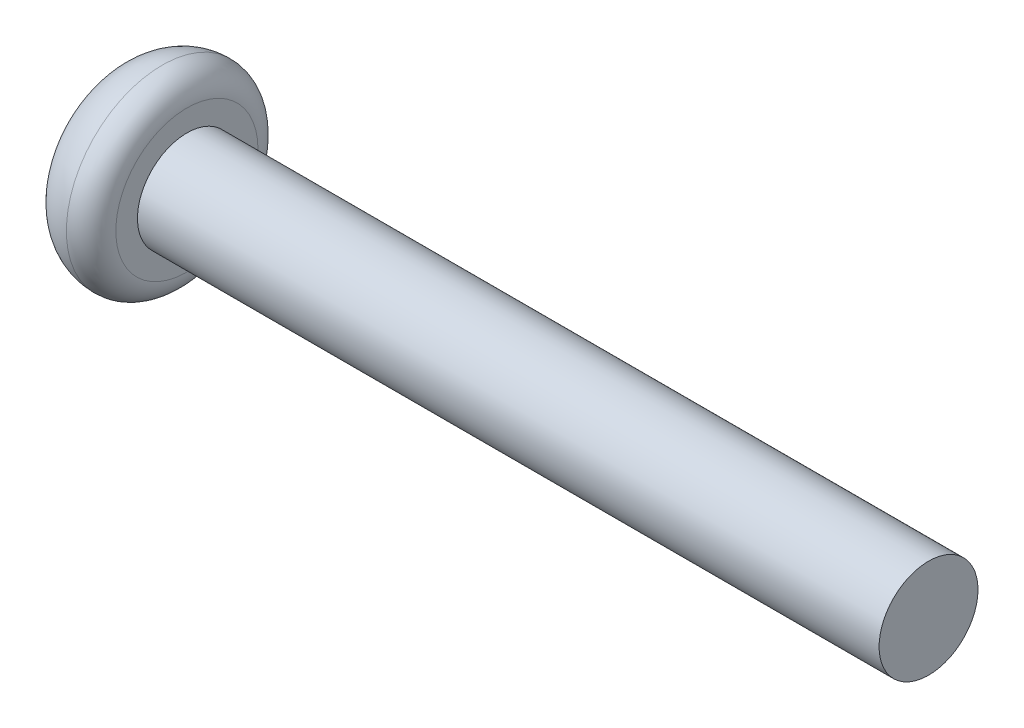
SolidWorks part; units mm, degrees
ref_plane "Front Plane" through (0, 0, 0) normal (0, 0, 1) x (1, 0, 0)
ref_plane "Top Plane" through (0, 0, 0) normal (0, 1, 0) x (1, 0, 0)
ref_plane "Right Plane" through (0, 0, 0) normal (1, 0, 0) x (0, 0, -1)
sketch "Sketch1" plane through (0, 0, 0) normal (0, 0, 1) x (1, 0, 0)
  line L0 (0, 0) -> (-4.4577, 0) construction
  line L1 (0, 0) -> (33, 0)
  line L2 (33, 0) -> (33, 2)
  line L3 (33, 2) -> (3, 2)
  line L4 (3, 2) -> (3, 2.875)
  line L6 (0, 1.875) -> (0, 0)
  arc A0 (3, 2.875) -> (2, 3.875) centre (2, 2.875) ccw
  arc A1 (2, 3.875) -> (0, 1.875) centre (2, 1.875) ccw
  dimension "D1" = 30
  dimension "D2" = 2
  dimension "D3" = 3
  dimension "D5" = 4
  dimension "D4" = 7.75
revolve "Revolve1" add sketch "Sketch1" angle 360 about L0
sketch "Sketch2" plane through (0, 0, 0) normal (-1, 0, 0) x (0, 0, 1)
  line L1 (-1.425, 1.425) -> (1.425, 1.425)
  line L2 (-1.425, 1.425) -> (-1.425, -1.425)
  line L3 (-1.425, -1.425) -> (1.425, -1.425)
  line L4 (1.425, 1.425) -> (1.425, -1.425)
  line L5 (-1.425, 1.425) -> (1.425, -1.425) construction
  line L6 (-1.425, -1.425) -> (1.425, 1.425) construction
  point P0 (0, 0)
  dimension "D1" = 2.85
extrude "Cut-Extrude1" cut sketch "Sketch2" against normal blind 2.5
equation "\"leng\"= 30"
equation "\"D1@Sketch1\"=\"leng\""
